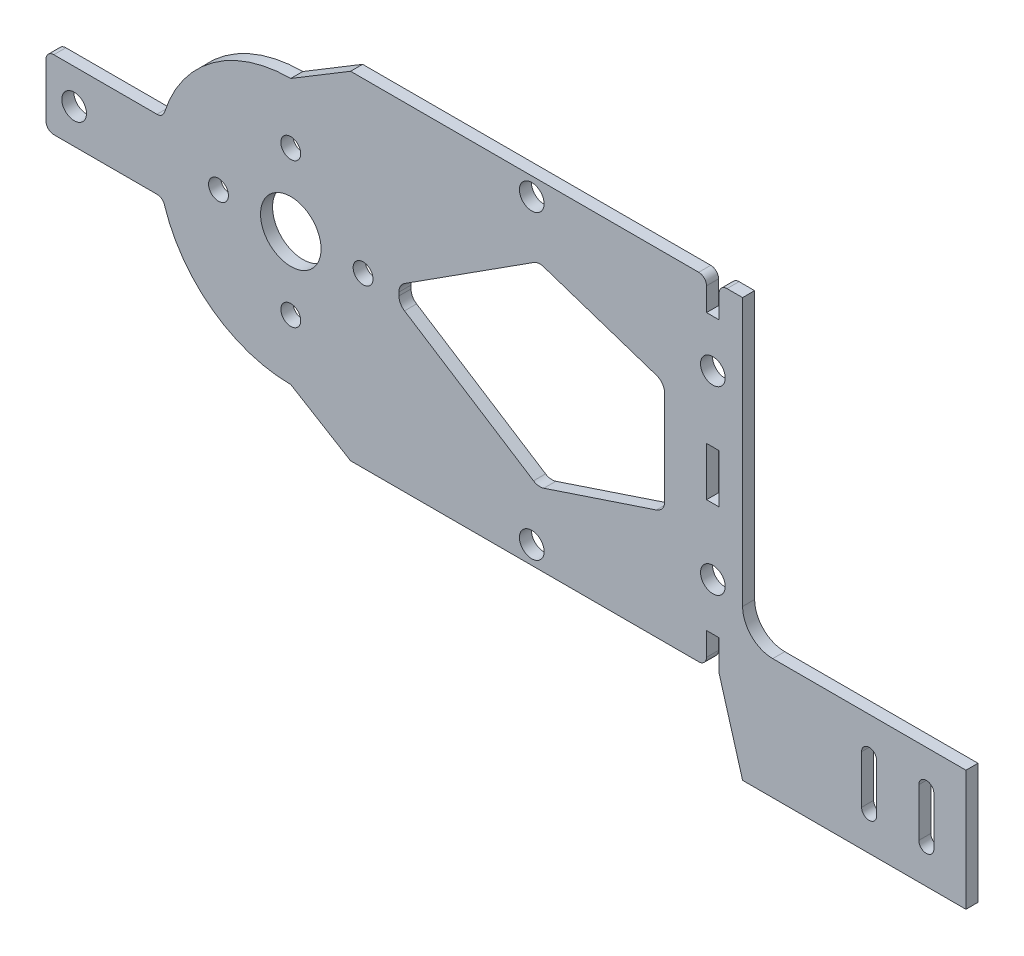
SolidWorks part; units mm, degrees
ref_plane "前视基准面" through (0, 0, 0) normal (0, 0, 1) x (1, 0, 0)
ref_plane "上视基准面" through (0, 0, 0) normal (0, 1, 0) x (1, 0, 0)
ref_plane "右视基准面" through (0, 0, 0) normal (1, 0, 0) x (0, 0, -1)
sketch "草图1" plane through (0, 0, 0) normal (0, 0, 1) x (1, 0, 0)
  line L0 (31.0657, 12.95) -> (31.0657, 17.05) construction
  line L1 (30.0157, 28) -> (32.1157, 28) construction
  line L2 (32.1157, -4.05) -> (30.0157, -4.05)
  line L3 (32.1157, -4.05) -> (32.1157, 4.05)
  line L4 (32.1157, 4.05) -> (30.0157, 4.05)
  line L5 (30.0157, -4.05) -> (30.0157, 4.05)
  line L6 (32.1157, -4.05) -> (30.0157, 4.05) construction
  line L7 (32.1157, 4.05) -> (30.0157, -4.05) construction
  line L8 (32.1157, 28) -> (32.1157, 22.85)
  line L9 (30.0157, 22.85) -> (32.1157, 22.85)
  line L10 (30.0157, 28) -> (30.0157, 22.85)
  line L11 (31.0657, 0) -> (29.7708, 0) construction
  line L12 (30.0157, -28) -> (32.1157, -28) construction
  line L13 (31.0657, -12.95) -> (31.0657, -17.05) construction
  line L14 (30.0157, -28) -> (30.0157, -22.85)
  line L15 (30.0157, -22.85) -> (32.1157, -22.85)
  line L16 (32.1157, -28) -> (32.1157, -22.85)
  line L17 (32.1157, -28) -> (36.001, -28) construction
  line L18 (36.001, -28) -> (36.001, 28) construction
  line L19 (36.001, 28) -> (32.1157, 28)
  line L23 (-38.999, -22.002) -> (-29.075, -28)
  line L25 (-38.999, 22.002) -> (-29.075, 28)
  line L29 (30.0157, -28) -> (-29.075, -28)
  line L30 (-29.075, 28) -> (30.0157, 28)
  line L31 (-29.075, -28) -> (-29.075, 28) construction
  line L41 (31.0657, -15) -> (31.0657, 15) construction
  line L42 (31.0657, 15) -> (1.001, 25) construction
  line L46 (1.001, -25) -> (31.0657, -15) construction
  line L47 (2.1009, -16.2032) -> (23.0657, -9.23)
  line L48 (23.0657, -9.23) -> (23.0657, 9.23)
  line L49 (23.0657, 9.23) -> (2.1009, 16.2032)
  line L50 (2.1009, 16.2032) -> (-21.0397, 1.3748)
  line L51 (-21.0397, 1.3748) -> (-21.0397, -1.3748)
  line L52 (-21.0397, -1.3748) -> (2.1009, -16.2032)
  line L53 (-74.9583, 0) -> (-38.999, 0) construction
  line L54 (-38.999, 0) -> (77.0107, 0) construction
  line L55 (-60.2364, -5.75) -> (-79.6313, -5.75)
  line L56 (-79.6313, -5.75) -> (-79.6313, 5.75)
  line L57 (-79.6313, 5.75) -> (-60.2364, 5.75)
  line L58 (36.001, -21.4019) -> (73.0775, -21.4019)
  line L59 (73.0775, -21.4019) -> (73.0775, -41.4019)
  line L60 (73.0775, -41.4019) -> (36.001, -41.4019)
  line L61 (36.001, -21.4019) -> (36.001, 28)
  line L62 (36.001, -41.4019) -> (36.001, -28) construction
  line L63 (-29.0397, 5.75) -> (-29.0397, -5.75) construction
  line L64 (-29.0397, -5.75) -> (1.001, -25) construction
  line L65 (1.001, 25) -> (-29.0397, 5.75) construction
  line L66 (57.001, -31.4019) -> (66.501, -31.4019) construction
  line L67 (66.501, -27.4019) -> (66.501, -35.4019) construction
  line L70 (57.001, -35.4019) -> (57.001, -27.4019) construction
  line L71 (55.751, -35.4019) -> (55.751, -27.4019)
  line L72 (58.251, -35.4019) -> (58.251, -27.4019)
  line L73 (67.751, -27.4019) -> (67.751, -35.4019)
  line L74 (65.251, -27.4019) -> (65.251, -35.4019)
  line L75 (32.1157, -28) -> (36.001, -41.4019)
  circle A0 centre (31.0657, 15) radius 2.05
  circle A1 centre (31.0657, -15) radius 2.05
  circle A3 centre (-38.999, 0) radius 5.025
  circle A6 centre (-38.999, 0) radius 12 construction
  circle A18 centre (-38.999, 0) radius 22.002 construction
  circle A30 centre (1.001, -25) radius 2.05
  circle A31 centre (1.001, 25) radius 2.05
  arc A32 (-38.999, -22.002) -> (-60.2364, -5.75) centre (-38.999, 0) cw
  arc A33 (-60.2364, 5.75) -> (-38.999, 22.002) centre (-38.999, 0) cw
  circle A34 centre (-74.9583, 0) radius 2.05
  arc A38 (55.751, -35.4019) -> (58.251, -35.4019) centre (57.001, -35.4019) ccw
  circle A39 centre (-50.999, 0) radius 1.65
  circle A40 centre (-38.999, 12) radius 1.65
  circle A41 centre (-26.999, 0) radius 1.65
  circle A42 centre (-38.999, -12) radius 1.65
  arc A43 (58.251, -27.4019) -> (55.751, -27.4019) centre (57.001, -27.4019) ccw
  arc A44 (67.751, -27.4019) -> (65.251, -27.4019) centre (66.501, -27.4019) ccw
  arc A45 (65.251, -35.4019) -> (67.751, -35.4019) centre (66.501, -35.4019) ccw
  point P4 (31.0657, 0)
  point P71 (66.501, -31.4019)
  point P79 (57.001, -31.4019)
  point P84 (36.001, -34.701)
  dimension "D3" = 10.05
  dimension "D4" = 75
  dimension "D5" = 35.9593
  dimension "D6" = 3.3
  dimension "D7" = 24
  dimension "D8" = 4
  dimension "D9" = 40
  dimension "D11" = 3
  dimension "D14" = 21
  dimension "D19" = 28
  dimension "D21" = 20
  dimension "D13" = 9.5
  dimension "D1" = 8.1
  dimension "D2" = 2.1
  dimension "D10" = 3
  dimension "D12" = 40
  dimension "D15" = 3.8853
  dimension "D16" = 2.1
  dimension "D18" = 30
  dimension "D17" = 8
extrude "凸台-拉伸1" add sketch "草图1" along normal blind 2
fillet "圆角1" radius 1.3 7 edges at (-79.6313, 5.75, 1) (-79.6313, -5.75, 1) (-60.2364, -5.75, 1) (-60.2364, 5.75, 1) (30.0157, -28, 1) (32.1157, 28, 1) (30.0157, 28, 1)
fillet "圆角2" radius 2 6 edges at (23.0657, 9.23, 1) (23.0657, -9.23, 1) (2.1009, -16.2032, 1) (2.1009, 16.2032, 1) (-21.0397, 1.3748, 1) (-21.0397, -1.3748, 1)
fillet "圆角3" radius 5 1 edges at (36.001, -21.4019, 1)
